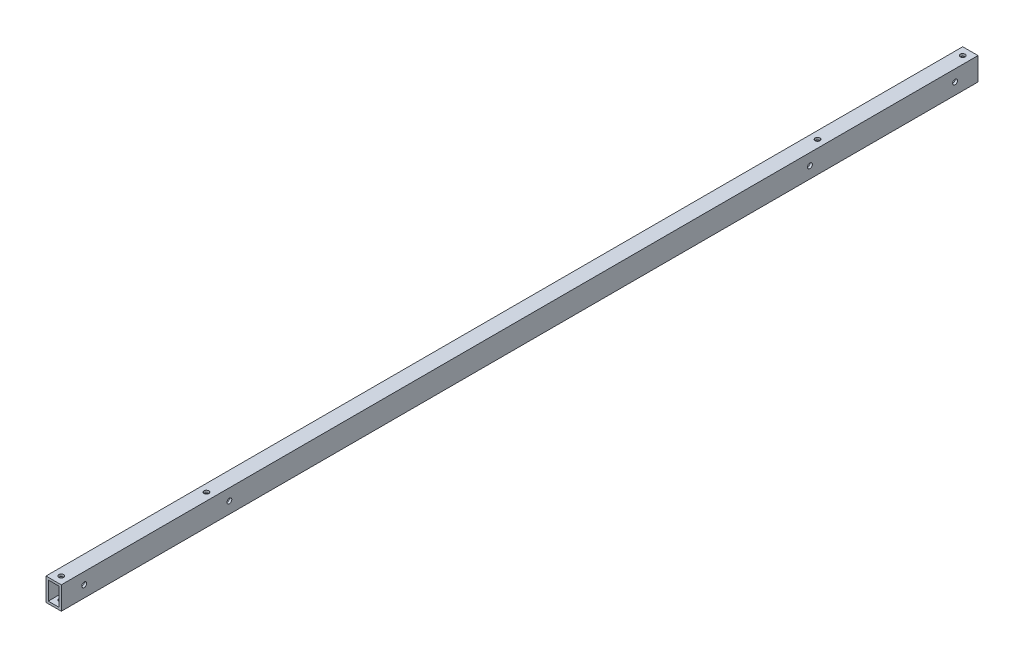
SolidWorks part; units mm, degrees
material "6063-T5"
ref_plane "正面" through (0, 0, 0) normal (0, 0, 1) x (1, 0, 0)
ref_plane "平面" through (0, 0, 0) normal (0, 1, 0) x (1, 0, 0)
ref_plane "右側面" through (0, 0, 0) normal (1, 0, 0) x (0, 0, -1)
sketch "ｽｹｯﾁ1" plane through (0, 0, 0) normal (0, 0, 1) x (1, 0, 0)
  line L1 (-5, -7.5) -> (5, -7.5)
  line L2 (-5, -7.5) -> (-5, 7.5)
  line L3 (-5, 7.5) -> (5, 7.5)
  line L4 (5, -7.5) -> (5, 7.5)
  line L5 (-5, -7.5) -> (5, 7.5) construction
  line L6 (-5, 7.5) -> (5, -7.5) construction
  point P0 (0, 0)
  dimension "D1" = 10
  dimension "D2" = 15
extrude "押し出し-薄板1" add sketch "ｽｹｯﾁ1" along normal blind 600 thin thin type one direction reverse wall 1.5
sketch "ｽｹｯﾁ2" plane through (0, 7.5, 0) normal (0, 1, 0) x (1, 0, 0)
  line L0 (0, 0) -> (0, -600) construction
  line L1 (5, -600) -> (-5, -600) construction
  line L2 (-5, -300) -> (5, -300) construction
  line L3 (-5, -600) -> (-5, 0) construction
  line L4 (5, -600) -> (5, 0) construction
  circle A0 centre (0, -595) radius 1.6
  circle A1 centre (0, -5) radius 1.6
  circle A2 centre (0, -500) radius 1.6
  circle A3 centre (0, -100) radius 1.6
  dimension "D1" = 5
  dimension "D2" = 3.2
  dimension "D3" = 95
extrude "ｶｯﾄ - 押し出し1" cut sketch "ｽｹｯﾁ2" against normal through all
sketch "ｽｹｯﾁ3" plane through (5, 0, 0) normal (1, 0, 0) x (0, 0, -1)
  line L0 (-600, 0) -> (0, 0) construction
  line L1 (-600, -7.5) -> (-600, 7.5) construction
  line L2 (0, -7.5) -> (0, 7.5) construction
  line L3 (-300, 7.5) -> (-300, -7.5) construction
  line L4 (-600, 7.5) -> (0, 7.5) construction
  line L5 (-600, -7.5) -> (0, -7.5) construction
  circle A0 centre (-585, 0) radius 1.6
  circle A1 centre (-15, 0) radius 1.6
  circle A2 centre (-490, 0) radius 1.6
  circle A3 centre (-110, 0) radius 1.6
  dimension "D1" = 15
  dimension "D2" = 3.2
  dimension "D3" = 110
extrude "ｶｯﾄ - 押し出し2" cut sketch "ｽｹｯﾁ3" against normal through all
